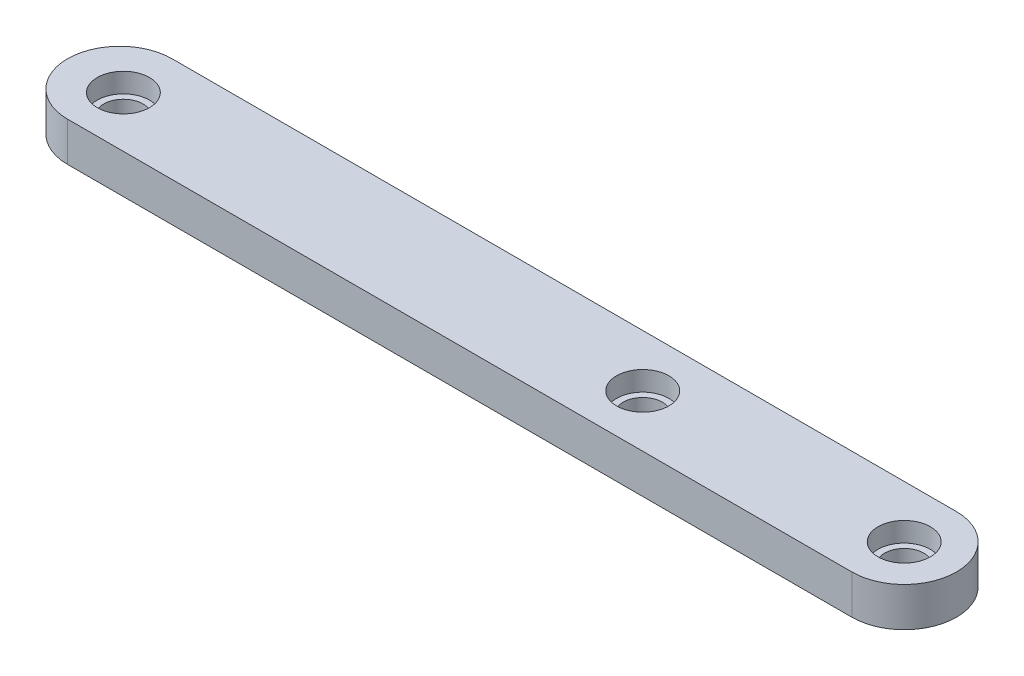
SolidWorks part; units mm, degrees
ref_plane "Front Plane" through (0, 0, 0) normal (0, 0, 1) x (1, 0, 0)
ref_plane "Top Plane" through (0, 0, 0) normal (0, 1, 0) x (1, 0, 0)
ref_plane "Right Plane" through (0, 0, 0) normal (1, 0, 0) x (0, 0, -1)
sketch "Sketch1" plane through (0, 0, 0) normal (0, 1, 0) x (1, 0, 0)
  line L0 (-56.2508, 0) -> (60, 0) construction
  line L1 (-60, -8) -> (60, -8)
  line L3 (-60, 8) -> (60, 8)
  line L11 (0, 8) -> (0, -8) construction
  circle A2 centre (-59.2433, -0.2116) radius 3
  circle A3 centre (60, 0) radius 3
  circle A4 centre (20, 0) radius 3
  arc A5 (-60, 8) -> (-60, -8) centre (-60, 0) ccw
  arc A7 (60, -8) -> (60, 8) centre (60, 0) ccw
  point P0 (0, 0)
  point P17 (0, 0)
  dimension "D3" = 6
  dimension "D4" = 6
  dimension "D5" = 6
  dimension "D8" = 16
  dimension "D1" = 120
  dimension "D2" = 8
  dimension "D6" = 60
  dimension "D7" = 40
extrude "Boss-Extrude1" add sketch "Sketch1" along normal blind 6
sketch "Sketch3" plane through (0, 6, 0) normal (0, 1, 0) x (1, 0, 0)
  circle A0 centre (-59.2433, -0.2116) radius 4
  circle A1 centre (20, 0) radius 4
  circle A2 centre (60, 0) radius 4
  dimension "D1" = 8
  dimension "D2" = 8
  dimension "D3" = 8
extrude "Cut-Extrude1" cut sketch "Sketch3" against normal blind 3
